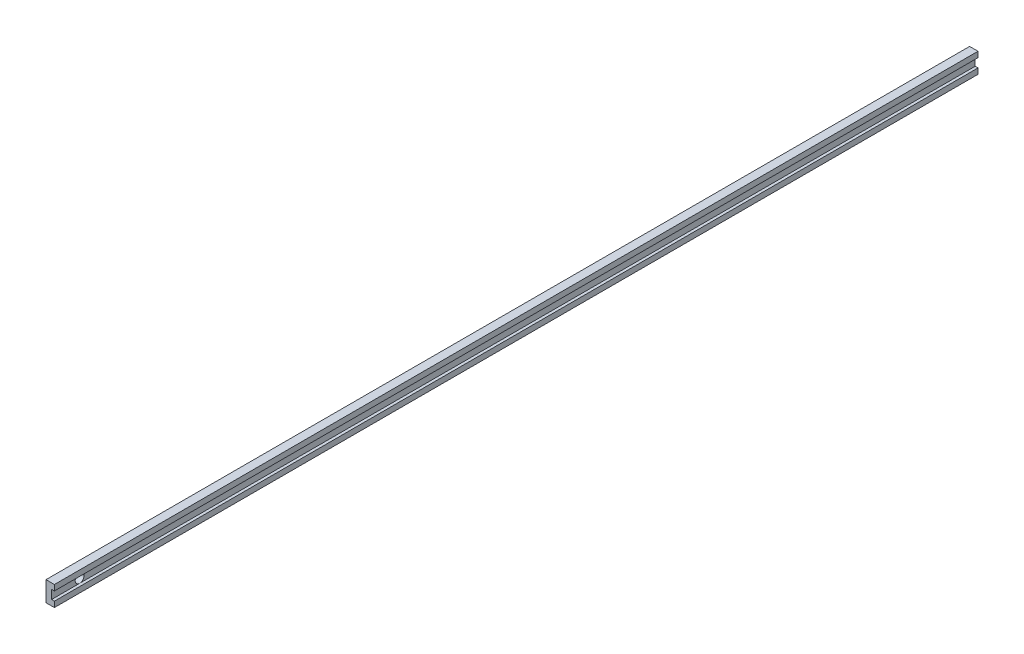
SolidWorks part; units mm, degrees
ref_plane "Front Plane" through (0, 0, 0) normal (0, 0, 1) x (1, 0, 0)
ref_plane "Top Plane" through (0, 0, 0) normal (0, 1, 0) x (1, 0, 0)
ref_plane "Right Plane" through (0, 0, 0) normal (1, 0, 0) x (0, 0, -1)
sketch "Sketch1" plane through (0, 0, 0) normal (0, 0, 1) x (1, 0, 0)
  line L0 (0, -5.3188) -> (0, -13.3188)
  line L1 (0, -13.3188) -> (2.54, -13.3188)
  line L2 (2.54, -13.3188) -> (2.54, -18.3988)
  line L3 (2.54, -18.3988) -> (-5.08, -18.3988)
  line L4 (-5.08, -18.3988) -> (-5.08, -0.2388)
  line L5 (-5.08, -0.2388) -> (2.54, -0.2388)
  line L6 (2.54, -0.2388) -> (2.54, -5.3188)
  line L7 (2.54, -5.3188) -> (0, -5.3188)
  dimension "D1" = 5.08
  dimension "D2" = 8
  dimension "D3" = 5.08
  dimension "D4" = 2.54
extrude "Boss-Extrude1" add sketch "Sketch1" along normal blind 838.2
hole_wizard "Ø8.0mm Dowel Hole1" positions "Sketch2" profile "Sketch3" hole size "Ø8.0" standard "ANSI Metric" end condition through all
sketch "Sketch2" plane through (-5.08, 0, 0) normal (-1, 0, 0) x (0, 0, 1)
  line L0 (812.8, -0.2388) -> (812.8, -18.3988) construction
  line L1 (838.2, -0.2388) -> (0, -0.2388) construction
  line L2 (838.2, -18.3988) -> (0, -18.3988) construction
  line L3 (838.2, -0.2388) -> (838.2, -18.3988) construction
  point P0 (812.8, -9.3188)
  point P11 (28.0492, -40.3372)
  dimension "D1" = 25.4
sketch "Sketch3" plane through (-5.08, -9.3188, 812.8) normal (0, 1, 0) x (0, 0, 1)
  line L0 (0, 0) -> (0, 7.62)
  line L1 (0, 7.62) -> (4, 7.62)
  line L2 (4, 7.62) -> (4, 0)
  line L5 (4, 0) -> (0, 0)
  line L11 (0, -6.35) -> (0, 107.95) construction
  dimension "Thru Hole Dia." = 8
  dimension "Thru Hole Depth" = 7.62
